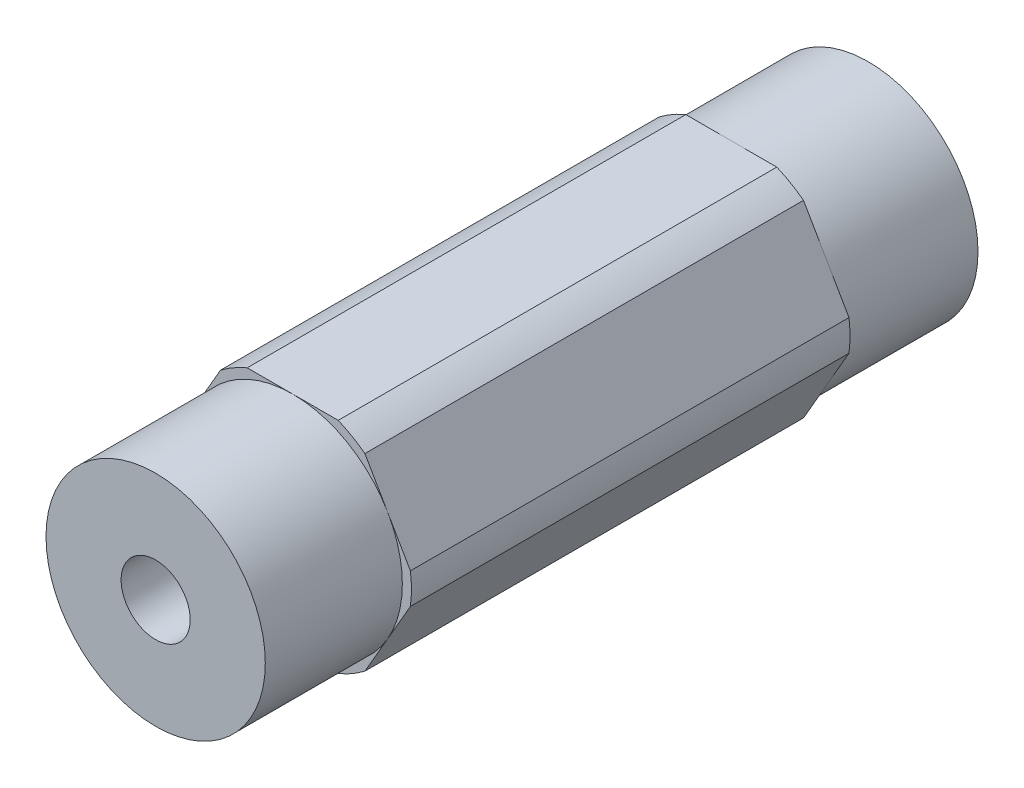
SolidWorks part; units mm, degrees
material "6061-T6 (SS)"
ref_plane "Front Plane" through (0, 0, 0) normal (0, 0, 1) x (1, 0, 0)
ref_plane "Top Plane" through (0, 0, 0) normal (0, 1, 0) x (1, 0, 0)
ref_plane "Right Plane" through (0, 0, 0) normal (1, 0, 0) x (0, 0, -1)
sketch "Sketch1" plane through (0, 0, 0) normal (0, 0, 1) x (1, 0, 0)
  line L1 (3.6662, 6.35) -> (-3.6662, 6.35)
  line L2 (-3.6662, 6.35) -> (-7.3323, 0)
  line L3 (-7.3323, 0) -> (-3.6662, -6.35)
  line L4 (-3.6662, -6.35) -> (3.6662, -6.35)
  line L5 (3.6662, -6.35) -> (7.3323, 0)
  line L6 (7.3323, 0) -> (3.6662, 6.35)
  circle A0 centre (0, 0) radius 6.35 construction
  circle A1 centre (0, 0) radius 2
  circle A2 centre (0, 0) radius 6.875
  point P1 (0, 6.35)
  dimension "D2" = 13.75
  dimension "D3" = 4
  dimension "D1" = 12.7
extrude "Boss-Extrude1" add sketch "Sketch1" along normal mid plane 25.4 contours L6 A2 L1 L2 L3 L4 L5 A1
sketch "Sketch4" plane through (0, 0, 12.7) normal (0, 0, 1) x (1, 0, 0)
  circle A0 centre (0, 0) radius 6.35
  circle A1 centre (0, 0) radius 2 construction
  circle A2 centre (0, 0) radius 2
  dimension "D1" = 12.7
extrude "Boss-Extrude2" add sketch "Sketch4" along normal blind 7.9375
mirror "Mirror1" about plane through (0, 0, 0) normal (0, 0, 1) of "Boss-Extrude2"
equation "\"D2@Sketch1\"=13.75mm"
equation "\"D3@Sketch1\"=4mm"
